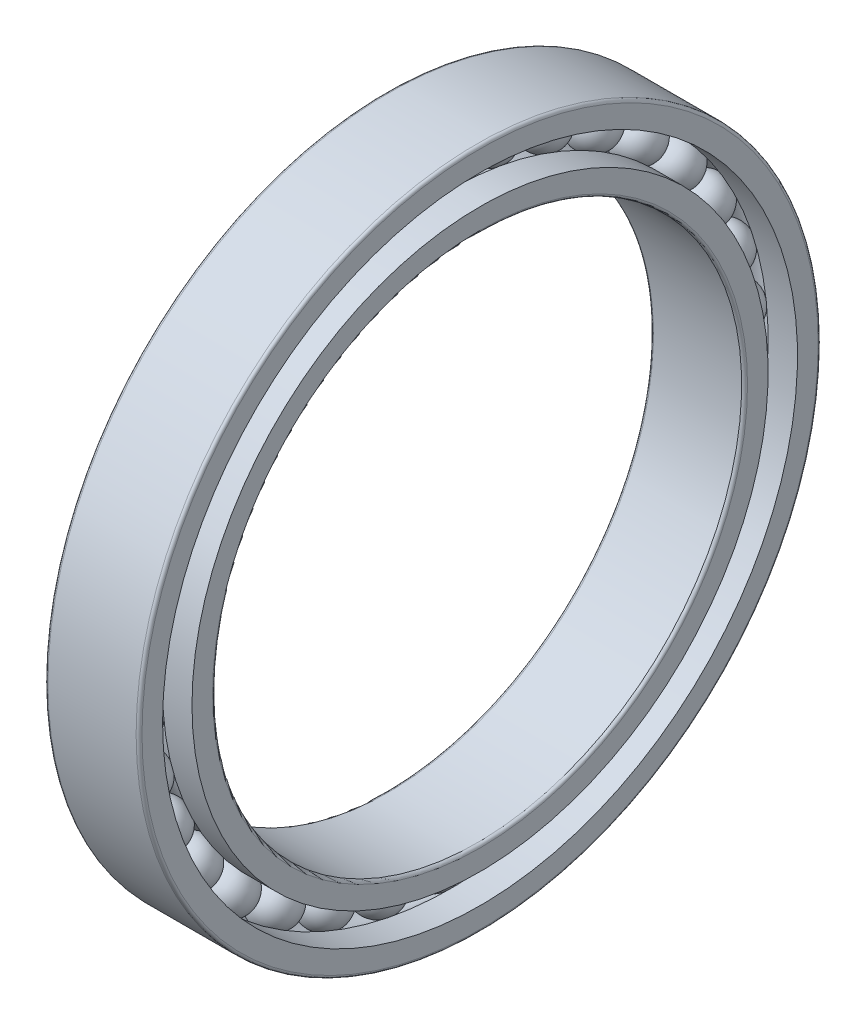
SolidWorks part; units mm, degrees
other "outer ring"
other "inner ring"
other "ball"
ref_plane "Front Plane" through (0, 0, 0) normal (0, 0, 1) x (1, 0, 0)
ref_plane "Top Plane" through (0, 0, 0) normal (0, 1, 0) x (1, 0, 0)
ref_plane "Right Plane" through (0, 0, 0) normal (1, 0, 0) x (0, 0, -1)
sketch "Sketch2" plane through (0, 0, 0) normal (0, 0, 1) x (1, 0, 0)
  line L0 (0, 0) -> (0, 29) construction
  line L1 (0, 0) -> (4, 0) construction
  line L2 (-3.75, 29) -> (3.75, 29)
  line L3 (-4, 28.75) -> (-4, 27)
  line L4 (-4, 27) -> (-1.4967, 27)
  line L5 (1.4967, 27) -> (4, 27)
  line L6 (4, 27) -> (4, 28.75)
  line L7 (-1.95, 25.75) -> (1.95, 25.75) construction
  line L8 (4, 24.5) -> (4, 22.75)
  line L9 (1.4967, 24.5) -> (4, 24.5)
  line L10 (-4, 24.5) -> (-1.4967, 24.5)
  line L11 (-4, 22.75) -> (-4, 24.5)
  line L12 (-3.75, 22.5) -> (3.75, 22.5)
  circle A0 centre (0, 25.75) radius 1.95 construction
  arc A1 (-1.4967, 27) -> (1.4967, 27) centre (0, 25.75) cw
  arc A2 (3.75, 29) -> (4, 28.75) centre (3.75, 28.75) cw
  arc A3 (-3.75, 29) -> (-4, 28.75) centre (-3.75, 28.75) ccw
  arc A4 (-3.75, 22.5) -> (-4, 22.75) centre (-3.75, 22.75) cw
  arc A5 (3.75, 22.5) -> (4, 22.75) centre (3.75, 22.75) ccw
  arc A6 (-1.4967, 24.5) -> (1.4967, 24.5) centre (0, 25.75) ccw
  point P9 (0, 29)
  point P16 (4, 29)
  point P19 (-4, 29)
  point P32 (-4, 22.5)
  point P33 (4, 22.5)
  point P34 (0, 22.5)
  dimension "D4" = 3.9
  dimension "D7" = 0.25
  dimension "D1" = 4
  dimension "D2" = 29
  dimension "D3" = 25.75
  dimension "D5" = 8
  dimension "D6" = 1.25
revolve "Revolve1" add sketch "Sketch2" angle 360 about L1
sketch "Sketch3" plane through (0, 0, 0) normal (0, 0, 1) x (1, 0, 0)
  line L0 (-1.95, 25.75) -> (1.95, 25.75)
  arc A0 (1.95, 25.75) -> (-1.95, 25.75) centre (0, 25.75) cw
revolve "Revolve2" add sketch "Sketch3" angle 360 about L7
pattern_circular "CirPattern1" count 34 over 360 about axis through (0, 0, 0) along (1, 0, 0) of bodies 103
